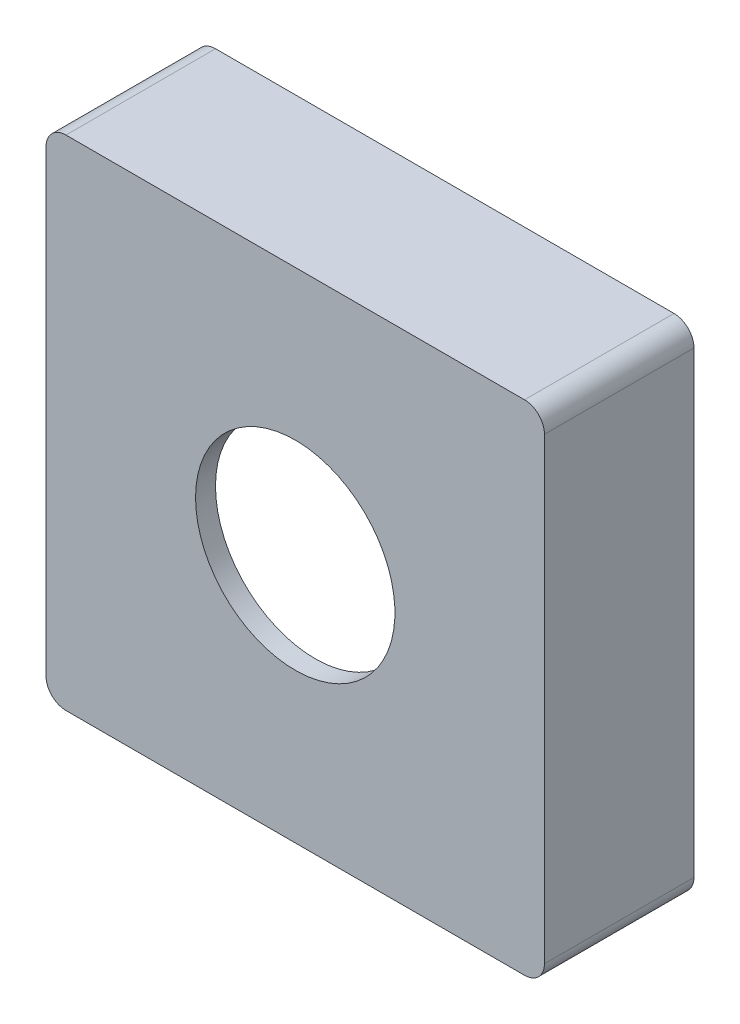
SolidWorks part; units mm, degrees
ref_plane "Front Plane" through (0, 0, 0) normal (1, 0, 0) x (0, 1, 0)
ref_plane "Top Plane" through (0, 0, 0) normal (0, 0, 1) x (0, 1, 0)
ref_plane "Right Plane" through (0, 0, 0) normal (0, 1, 0) x (-1, 0, 0)
sketch "Sketch1" plane through (0, 0, 0) normal (0, 0, 1) x (0, 1, 0)
  line L1 (-25, -25) -> (25, -25)
  line L2 (-25, -25) -> (-25, 25)
  line L3 (-25, 25) -> (25, 25)
  line L4 (25, -25) -> (25, 25)
  line L5 (-25, -25) -> (25, 25) construction
  line L6 (-25, 25) -> (25, -25) construction
  point P0 (0, 0)
  dimension "D1" = 50
  dimension "D2" = 50
extrude "Boss-Extrude1" add sketch "Sketch1" along normal blind 15
shell "Shell2" thickness 2
sketch "Sketch3" plane through (0, 0, 15) normal (0, 0, 1) x (1, 0, 0)
  circle A1 centre (0, 0) radius 10
  dimension "D1" = 20
extrude "Cut-Extrude1" cut sketch "Sketch3" against normal through all both and the other way through all
fillet "Fillet1" radius 2 4 edges at (-23, -23, 6.5) (-23, 23, 6.5) (23, -23, 6.5) (23, 23, 6.5)
fillet "Fillet3" radius 2 4 edges at (-25, -25, 7.5) (-25, 25, 7.5) (25, 25, 7.5) (25, -25, 7.5)
sketch "Sketch5" plane through (0, 0, 13) normal (0, 0, -1) x (1, 0, 0)
  circle A0 centre (17.5, 10) radius 2.5
  circle A1 centre (17.5, 10) radius 1.5
  dimension "D3" = 5
  dimension "4" = 3
  dimension "D1" = 10
  dimension "D2" = 17.5
extrude "Boss-Extrude2" add sketch "Sketch5" along normal blind 3
pattern_linear "LPattern2" count 2 spacing 20 along (0, 1, 0) count 2 spacing 35 along (-1, 0, 0) of "Boss-Extrude2"
